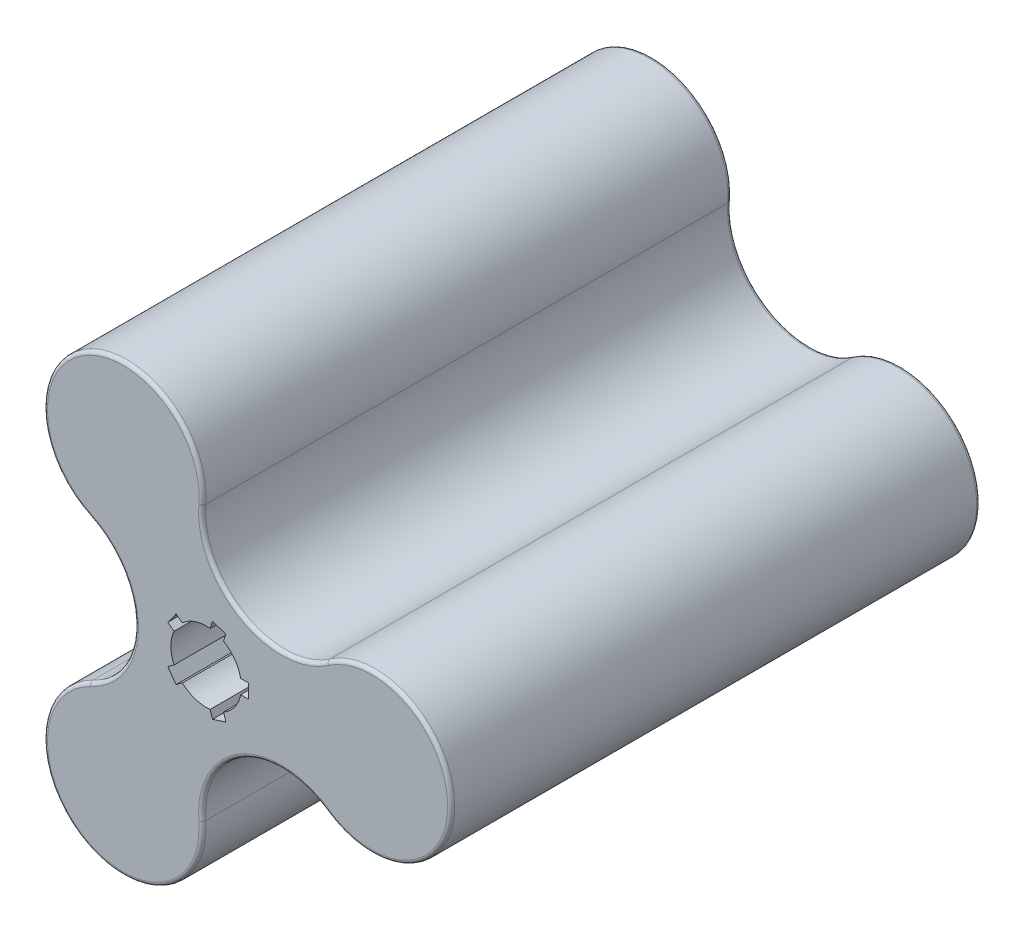
SolidWorks part; units mm, degrees
ref_plane "Front Plane" through (0, 0, 0) normal (0, 0, 1) x (1, 0, 0)
ref_plane "Top Plane" through (0, 0, 0) normal (0, 1, 0) x (1, 0, 0)
ref_plane "Right Plane" through (0, 0, 0) normal (1, 0, 0) x (0, 0, -1)
sketch "Sketch1" plane through (0, 0, 0) normal (0, 0, 1) x (1, 0, 0)
  line L0 (0, 0) -> (0, -13646.2338) construction
  line L1 (0, 0) -> (13646.2338, 0) construction
  line L2 (0.57, -8.2265) -> (1.8061, -12.0307)
  line L3 (8, 2) -> (12, 2)
  line L4 (8, 2) -> (8, -2)
  line L5 (8, -2) -> (12, -2)
  line L6 (12, 2) -> (12, -2)
  line L7 (8, 2) -> (12, -2) construction
  line L8 (8, -2) -> (12, 2) construction
  line L9 (5.6103, -10.7946) -> (1.8061, -12.0307)
  line L10 (4.3742, -6.9904) -> (0.57, -8.2265)
  line L11 (4.3742, -6.9904) -> (5.6103, -10.7946)
  line L12 (-7.6477, -3.0842) -> (-10.8838, -5.4354)
  line L13 (-8.5326, -8.6715) -> (-10.8838, -5.4354)
  line L14 (-5.2966, -6.3203) -> (-7.6477, -3.0842)
  line L15 (-5.2966, -6.3203) -> (-8.5326, -8.6715)
  line L16 (-5.2966, 6.3203) -> (-8.5326, 8.6715)
  line L17 (-10.8838, 5.4354) -> (-8.5326, 8.6715)
  line L18 (-7.6477, 3.0842) -> (-5.2966, 6.3203)
  line L19 (-7.6477, 3.0842) -> (-10.8838, 5.4354)
  line L20 (4.3742, 6.9904) -> (5.6103, 10.7946)
  line L21 (1.8061, 12.0307) -> (5.6103, 10.7946)
  line L22 (0.57, 8.2265) -> (4.3742, 6.9904)
  line L23 (0.57, 8.2265) -> (1.8061, 12.0307)
  circle A0 centre (0, 0) radius 10
  circle A1 centre (47, 0) radius 22.5
  circle A2 centre (-23.5, -40.7032) radius 22.5
  circle A3 centre (-23.5, 40.7032) radius 22.5
  arc A4 (-1.0775, 38.8368) -> (34.1725, 18.4852) centre (21.3449, 36.9705) ccw
  arc A5 (34.1725, -18.4852) -> (-1.0775, -38.8368) centre (21.3449, -36.9705) ccw
  arc A6 (-33.0949, -20.3516) -> (-33.0949, 20.3516) centre (-42.6898, 0) ccw
  point P15 (0, 0)
  point P17 (10, 0)
  point P25 (0, 0)
  point P29 (0, 0)
  point P47 (0, 0)
  dimension "D1" = 20
  dimension "D2" = 45
  dimension "D5" = 22.5
  dimension "D3" = 47
  dimension "D7" = 21.3449
  dimension "D8" = 33.0949
  dimension "D9" = 4
  dimension "D10" = 4
  dimension "D11" = 5
  dimension "D4" = 3
  dimension "D6" = 3
extrude "Boss-Extrude1" add sketch "Sketch1" along normal blind 150 contours A1 | A2 | A3 | A6 A2 A5 A1 A4 A3 A0 L3 L6 L5 L11 L9 L2 L15 L13 L12 L19 L17 L16 L23 L21 L20
fillet "Fillet1" radius 1 12 edges at (10.0949, 17.4849, 0) (10.0949, 17.4849, 150) (69.5, 0, 0) (69.5, 0, 150) (10.0949, -17.4849, 0) (10.0949, -17.4849, 150) (-34.75, -60.1888, 0) (-34.75, -60.1888, 150) (-20.1898, 0, 0) (-20.1898, 0, 150) (-34.75, 60.1888, 0) (-34.75, 60.1888, 150)
